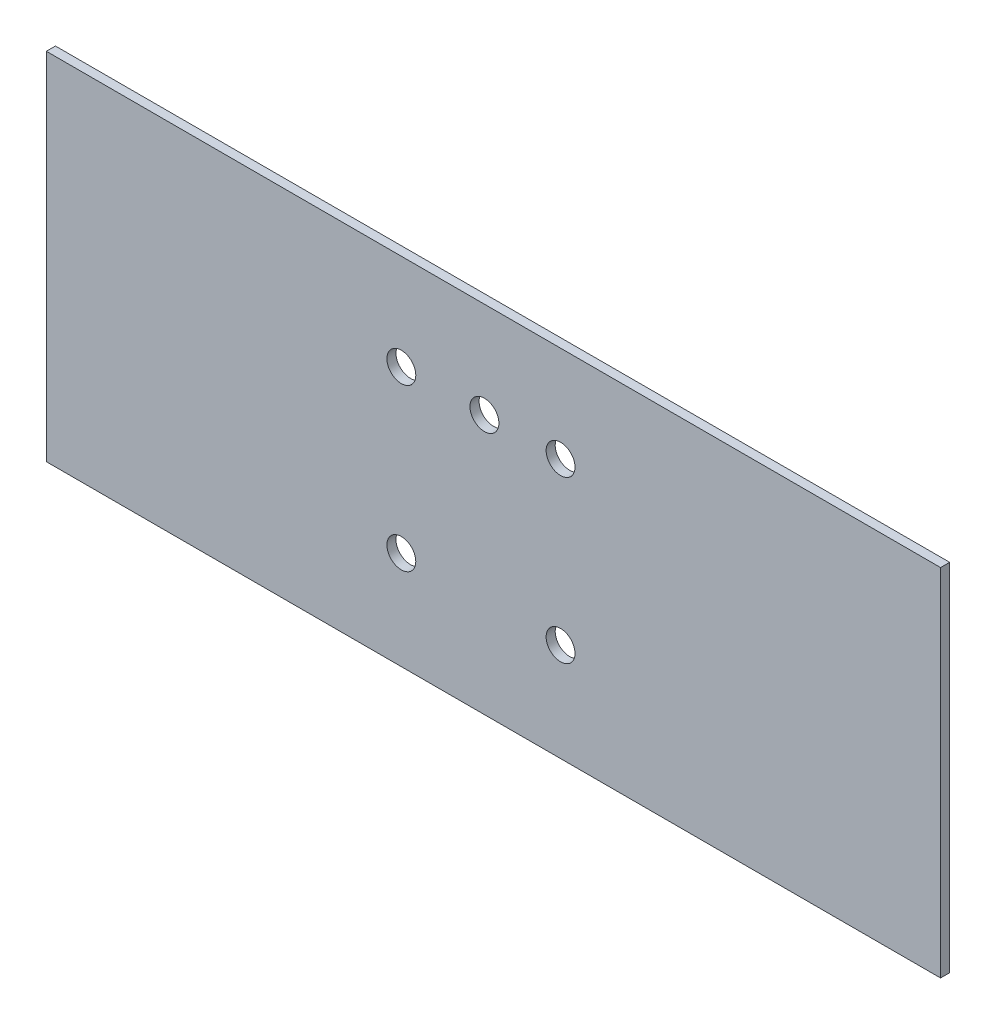
SolidWorks part; units mm, degrees
material "Hierro dúctil"
ref_plane "Alzado" through (0, 0, 0) normal (0, 0, 1) x (1, 0, 0)
ref_plane "Planta" through (0, 0, 0) normal (0, 1, 0) x (1, 0, 0)
ref_plane "Vista lateral" through (0, 0, 0) normal (1, 0, 0) x (0, 0, -1)
sketch "Croquis1" plane through (0, 0, 0) normal (0, 0, 1) x (1, 0, 0)
  line L1 (-141.071, -148.2084) -> (252.0591, -148.2084)
  line L2 (-141.071, -148.2084) -> (-141.071, 8.0669)
  line L3 (-141.071, 8.0669) -> (252.0591, 8.0669)
  line L4 (252.0591, -148.2084) -> (252.0591, 8.0669)
  circle A4 centre (15, -105) radius 6.35
  circle A5 centre (85, -105) radius 6.35
  circle A6 centre (85, -34.0899) radius 6.35
  circle A7 centre (15, -34.0899) radius 6.35
  circle A8 centre (51.5322, -34.0899) radius 6.35 construction
  circle A9 centre (51.5322, -34.0899) radius 6.35
  dimension "D1" = 156.2753
  dimension "D2" = 393.13
extrude "Saliente-Extruir1" add sketch "Croquis1" along normal blind 4 contours L3 L4 L1 L2
